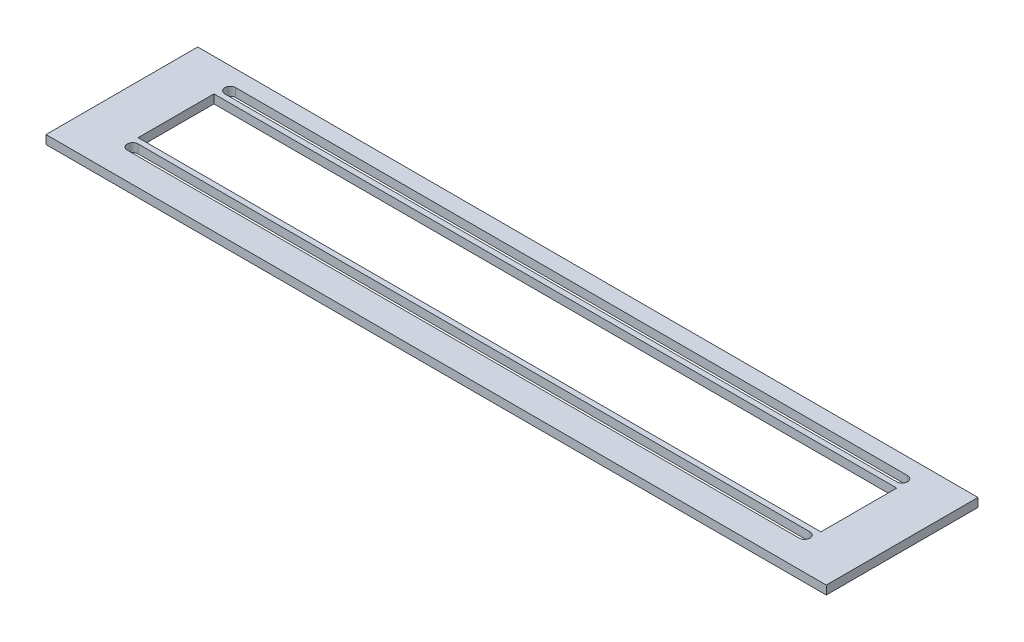
SolidWorks part; units mm, degrees
material "A-玻璃纤维"
ref_plane "前视基准面" through (0, 0, 0) normal (0, 0, 1) x (1, 0, 0)
ref_plane "上视基准面" through (0, 0, 0) normal (0, 1, 0) x (1, 0, 0)
ref_plane "右视基准面" through (0, 0, 0) normal (1, 0, 0) x (0, 0, -1)
other "Configuration Table"
sketch "草图1" plane through (0, 0, 0) normal (0, 1, 0) x (1, 0, 0)
  line L0 (0, 0) -> (0, -70)
  line L1 (0, -70) -> (360, -70)
  line L2 (360, -70) -> (360, 0)
  line L3 (360, 0) -> (0, 0)
  dimension "D1" = 360
  dimension "D2" = 70
extrude "凸台-拉伸1" add sketch "草图1" along normal blind 4
sketch "草图2" plane through (0, 4, 0) normal (0, 1, 0) x (1, 0, 0)
  line L0 (0, -70) -> (0, -55)
  line L1 (0, 0) -> (0, -70) construction
  line L2 (0, -55) -> (360, -55)
  line L3 (360, -70) -> (360, 0) construction
  line L4 (0, -55) -> (25, -55)
  line L5 (360, -55) -> (335, -55)
  line L6 (335, -55) -> (25, -55) construction
  line L7 (335, -57.5) -> (25, -57.5)
  line L8 (335, -52.5) -> (25, -52.5)
  arc A0 (335, -57.5) -> (335, -52.5) centre (335, -55) ccw
  arc A1 (25, -52.5) -> (25, -57.5) centre (25, -55) ccw
  point P8 (180, -55)
  dimension "D1" = 15
  dimension "D2" = 25
extrude "切除-拉伸1" cut sketch "草图2" against normal through all contours L8 A1 L4 L2 A0 | L4 A1 L7 A0 L2
sketch "草图3" plane through (0, 0, 0) normal (0, -1, 0) x (1, 0, 0)
  line L0 (25, 55) -> (25, 0)
  line L1 (360, 0) -> (0, 0) construction
  line L2 (25, 0) -> (25, 10)
  line L3 (25, 10) -> (360, 10)
  line L4 (360, 70) -> (360, 0) construction
  line L5 (360, 10) -> (335, 10)
  line L6 (25, 10) -> (335, 10) construction
  line L7 (25, 12.5) -> (335, 12.5)
  line L8 (25, 7.5) -> (335, 7.5)
  arc A0 (25, 12.5) -> (25, 7.5) centre (25, 10) ccw
  arc A1 (335, 7.5) -> (335, 12.5) centre (335, 10) ccw
  point P5 (180, 10)
  dimension "D1" = 10
extrude "切除-拉伸2" cut sketch "草图3" against normal through all contours L3 A1 L7 L0
sketch "草图4" plane through (0, 0, 0) normal (0, -1, 0) x (1, 0, 0)
  line L0 (25, 55) -> (25, 10)
  line L1 (25, 10) -> (25, 15)
  line L2 (25, 15) -> (335, 15)
  line L3 (25, 55) -> (25, 50)
  line L4 (25, 50) -> (335, 50)
  line L5 (335, 50) -> (335, 15)
  line L6 (22.5, 55) -> (22.5, 10)
  line L7 (25, 50) -> (22.5, 50)
  line L8 (25, 15) -> (22.5, 15)
  line L9 (337.5, 55) -> (337.5, 10)
  line L10 (335, 15) -> (337.5, 15)
  line L11 (335, 50) -> (337.5, 50)
  arc A0 (25, 57.5) -> (25, 52.5) centre (25, 55) ccw construction
  arc A1 (25, 12.5) -> (25, 7.5) centre (25, 10) ccw construction
  arc A2 (335, 52.5) -> (335, 57.5) centre (335, 55) ccw construction
  arc A3 (335, 7.5) -> (335, 12.5) centre (335, 10) ccw construction
extrude "切除-拉伸3" cut sketch "草图4" against normal through all contours L5 L4 L0 L2 | L8 L0 L7 L6 | L11 L5 L10 L9
